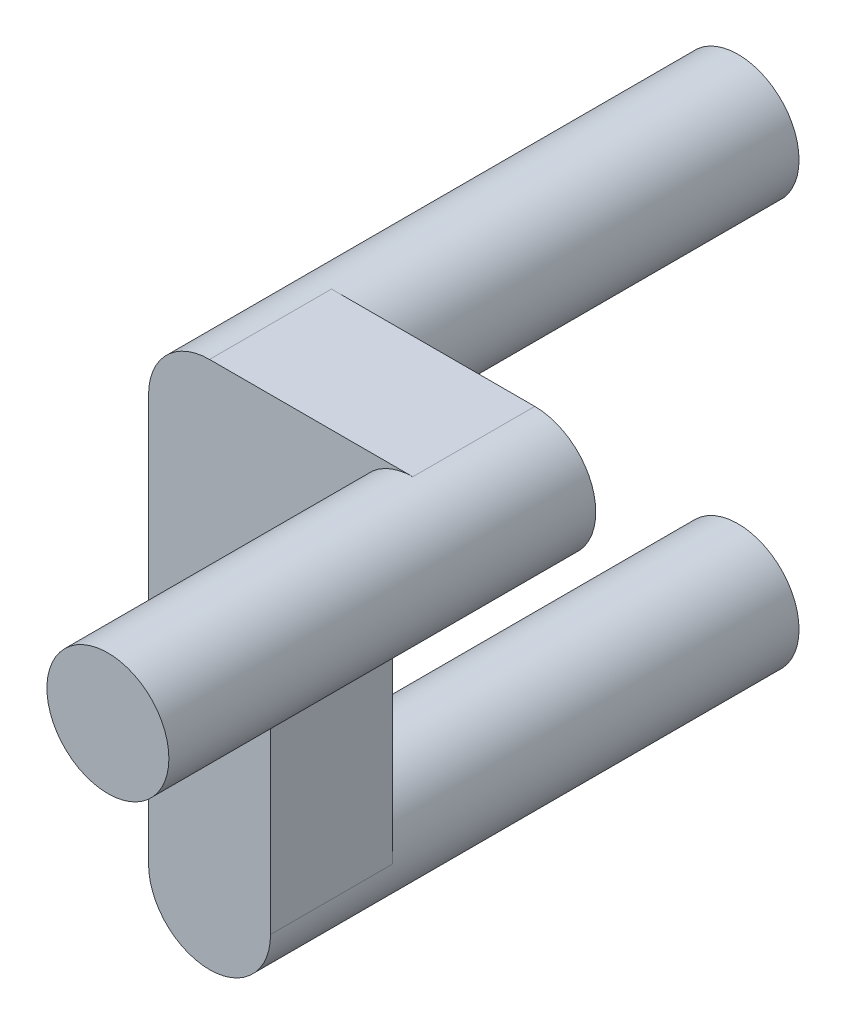
SolidWorks part; units mm, degrees
ref_plane "Front Plane" through (0, 0, 0) normal (0, 0, 1) x (1, 0, 0)
ref_plane "Top Plane" through (0, 0, 0) normal (0, 1, 0) x (1, 0, 0)
ref_plane "Right Plane" through (0, 0, 0) normal (1, 0, 0) x (0, 0, -1)
sketch "Sketch2" plane through (0, 0, 0) normal (0, 0, 1) x (1, 0, 0)
  line L0 (0, 0) -> (0, -50.8)
  circle A0 centre (0, 0) radius 7.62
  circle A1 centre (0, -50.8) radius 7.62
  dimension "D1" = 15.24
  dimension "D2" = 15.24
extrude "Boss-Extrude1" add sketch "Sketch2" along normal blind 50.8
sketch "Sketch4" plane through (0, 0, 50.8) normal (0, 0, 1) x (1, 0, 0)
  line L1 (-7.62, -7.62) -> (7.62, -7.62)
  line L2 (-7.62, -7.62) -> (-7.62, 7.62)
  line L3 (-7.62, 7.62) -> (7.62, 7.62)
  line L4 (7.62, -7.62) -> (7.62, 7.62)
  circle A1 centre (0, 0) radius 7.62 construction
extrude "Boss-Extrude3" add sketch "Sketch4" along normal blind 15.24
sketch "Sketch6" plane through (7.62, 0, 0) normal (1, 0, 0) x (0, 0, -1)
  line L1 (-66.04, 7.62) -> (-50.8, 7.62)
  line L2 (-66.04, 7.62) -> (-66.04, -7.62)
  line L3 (-66.04, -7.62) -> (-50.8, -7.62)
  line L4 (-50.8, 7.62) -> (-50.8, -7.62)
extrude "Boss-Extrude4" add sketch "Sketch6" along normal blind 25.4
sketch "Sketch7" plane through (0, 0, 66.04) normal (0, 0, 1) x (1, 0, 0)
  line L0 (-7.62, -7.62) -> (33.02, -7.62) construction
  line L1 (33.02, 7.62) -> (17.78, 7.62)
  line L2 (33.02, 7.62) -> (33.02, -7.62)
  line L3 (33.02, -7.62) -> (17.78, -7.62)
  line L4 (17.78, 7.62) -> (17.78, -7.62)
  circle A0 centre (25.4, 0) radius 7.62
  line M6 (-7.62, -7.62) -> (33.02, -7.62)
extrude "Boss-Extrude6" add sketch "Sketch7" along normal blind 38.1 contours A0 M6
sketch "Sketch8" plane through (0, 0, 0) normal (0, 0, -1) x (-1, 0, 0)
  line L0 (0, -7.62) -> (-33.02, -7.62) construction
  line L1 (7.62, 7.62) -> (-7.6884, 7.62)
  line L2 (7.62, 7.62) -> (7.62, -7.62)
  line L3 (7.62, -7.62) -> (-7.6884, -7.62)
  line L4 (-7.6884, 7.62) -> (-7.6884, -7.62)
  circle A0 centre (0, 0) radius 7.62
  circle M5 centre (0, 0) radius 7.62
extrude "Cut-Extrude1" cut sketch "Sketch8" against normal blind 86.106 contours L2 L1 M5 | L3 L2 M5
sketch "Sketch9" plane through (0, 0, 104.14) normal (0, 0, 1) x (1, 0, 0)
  line L0 (0, -7.62) -> (25.4, -7.62) construction
  line L1 (33.02, 7.62) -> (16.9894, 7.62)
  line L2 (33.02, 7.62) -> (33.02, -7.62)
  line L3 (33.02, -7.62) -> (16.9894, -7.62)
  line L4 (16.9894, 7.62) -> (16.9894, -7.62)
  circle A0 centre (25.4, 0) radius 7.62
  circle M1 centre (25.4, 0) radius 7.62
extrude "Cut-Extrude2" cut sketch "Sketch9" against normal blind 86.106 contours L2 L1 M1 | L3 L2 M1
sketch "Sketch10" plane through (0, -7.62, 0) normal (0, -1, 0) x (1, 0, 0)
  line L0 (-7.62, 66.04) -> (-7.62, 0) construction
  line L1 (7.62, 50.8) -> (-7.62, 50.8)
  line L2 (7.62, 50.8) -> (7.62, 66.04)
  line L3 (7.62, 66.04) -> (-7.62, 66.04)
  line L4 (-7.62, 50.8) -> (-7.62, 66.04)
extrude "Boss-Extrude7" add sketch "Sketch10" along normal blind 50.8 and the other way blind 15.24
sketch "Sketch13" plane through (0, 0, 0) normal (0, 0, -1) x (-1, 0, 0)
  line L0 (-7.62, -7.62) -> (-7.62, -50.8) construction
  line L1 (7.62, -58.42) -> (-7.62, -58.42)
  line L2 (7.62, -58.42) -> (7.62, -43.18)
  line L3 (7.62, -43.18) -> (-7.62, -43.18)
  line L4 (-7.62, -58.42) -> (-7.62, -43.18)
  line L6 (7.62, 7.62) -> (-7.62, 7.62)
  line L7 (7.62, 7.62) -> (7.62, -7.62)
  line L8 (7.62, -7.62) -> (-7.62, -7.62)
  line L9 (-7.62, 7.62) -> (-7.62, -7.62)
  circle A0 centre (0, -50.8) radius 7.62
  circle A1 centre (0, 0) radius 7.62
  circle M5 centre (0, -50.8) radius 7.62
extrude "Cut-Extrude6" cut sketch "Sketch13" against normal blind 92.456 contours A1 L7 L6 | L1 L2 M5 | L4 L1 M5
